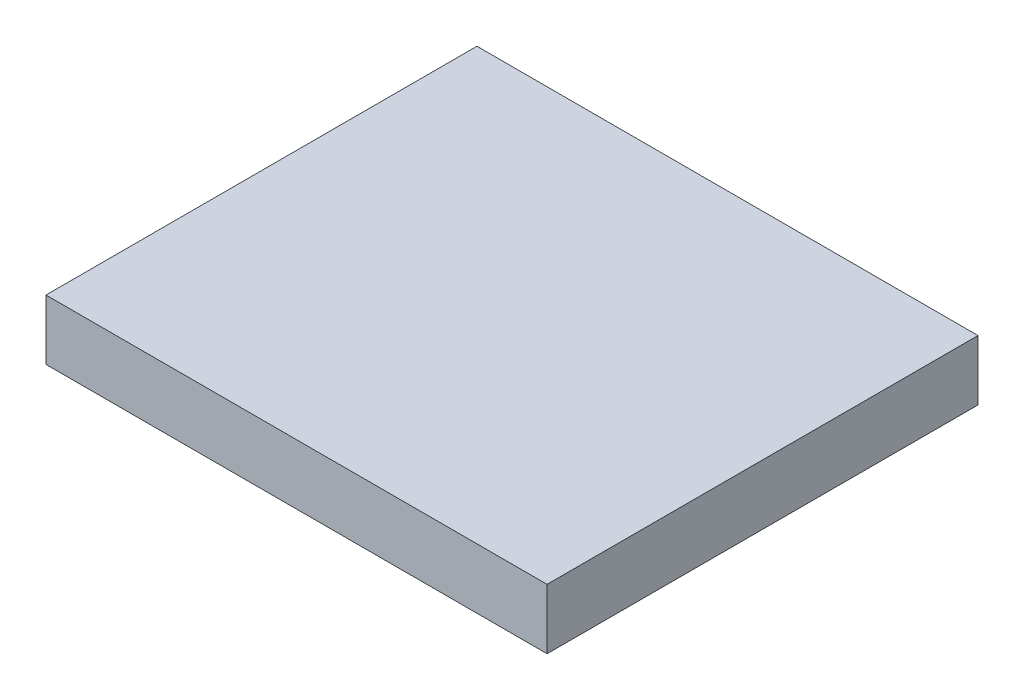
SolidWorks part; units mm, degrees
ref_plane "Front Plane" through (0, 0, 0) normal (0, 0, 1) x (1, 0, 0)
ref_plane "Top Plane" through (0, 0, 0) normal (0, 1, 0) x (1, 0, 0)
ref_plane "Right Plane" through (0, 0, 0) normal (1, 0, 0) x (0, 0, -1)
sketch "Sketch1" plane through (0, 0, 0) normal (0, 1, 0) x (1, 0, 0)
  line L1 (-25, 21.5) -> (25, 21.5)
  line L2 (-25, 21.5) -> (-25, -21.5)
  line L3 (-25, -21.5) -> (25, -21.5)
  line L4 (25, 21.5) -> (25, -21.5)
  line L5 (-25, 21.5) -> (25, -21.5) construction
  line L6 (-25, -21.5) -> (25, 21.5) construction
  point P0 (0, 0)
  dimension "D1" = 50
  dimension "D2" = 43
extrude "Boss-Extrude1" add sketch "Sketch1" along normal blind 6
